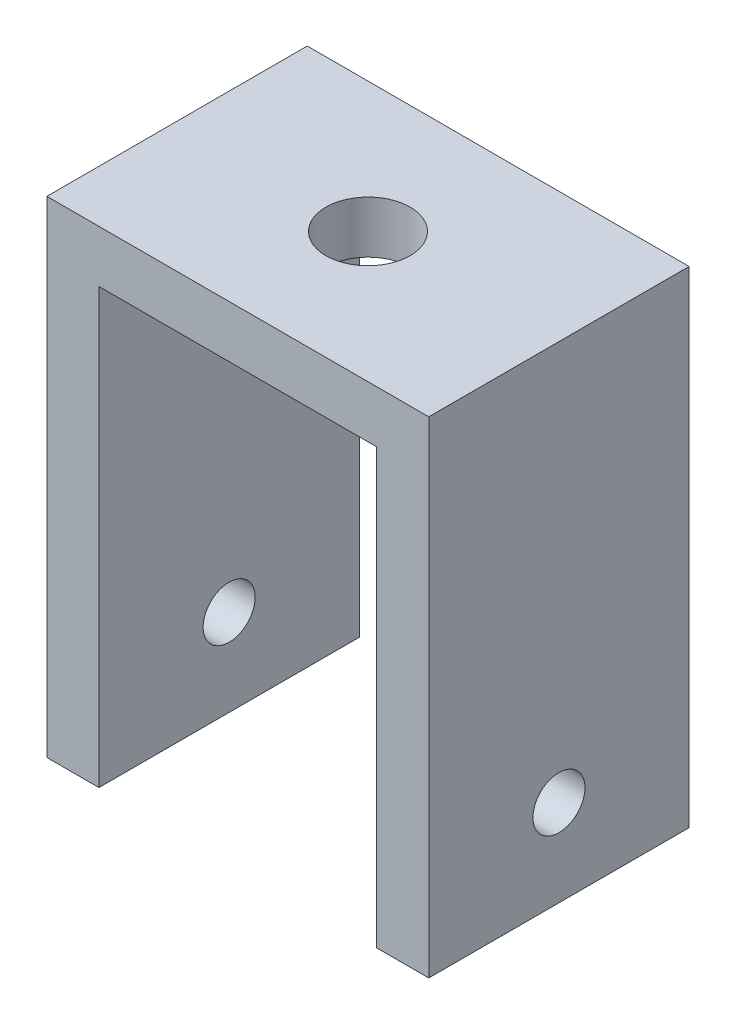
SolidWorks part; units mm, degrees
ref_plane "前视基准面" through (0, 0, 0) normal (0, 0, 1) x (1, 0, 0)
ref_plane "上视基准面" through (0, 0, 0) normal (0, 1, 0) x (1, 0, 0)
ref_plane "右视基准面" through (0, 0, 0) normal (1, 0, 0) x (0, 0, -1)
sketch "草图1" plane through (0, 0, 0) normal (0, 0, 1) x (1, 0, 0)
  line L0 (0, 0) -> (8, 0)
  line L1 (8, 0) -> (8, -25)
  line L2 (0, 0) -> (-8, 0)
  line L3 (-8, 0) -> (-8, -25)
  line L4 (11, 3) -> (11, -25)
  line L5 (0, 3) -> (11, 3)
  line L6 (0, 3) -> (-11, 3)
  line L7 (-11, 3) -> (-11, -25)
  line L8 (-8, -25) -> (-11, -25)
  line L9 (8, -25) -> (11, -25)
  dimension "D1" = 25
  dimension "D2" = 8
  dimension "D3" = 8
  dimension "D4" = 3
extrude "凸台-拉伸1" add sketch "草图1" along normal blind 15
sketch "草图2" plane through (11, 0, 0) normal (1, 0, 0) x (0, 0, -1)
  line L0 (-15, -25) -> (0, -25) construction
  circle A0 centre (-7.5, -20) radius 1.5
  dimension "D1" = 3
  dimension "D2" = 5
extrude "切除-拉伸1" cut sketch "草图2" against normal through all
sketch "草图3" plane through (0, 3, 0) normal (0, 1, 0) x (1, 0, 0)
  circle A0 centre (0, -7.5) radius 2.425
  dimension "D1" = 4.85
extrude "切除-拉伸2" cut sketch "草图3" against normal through all
